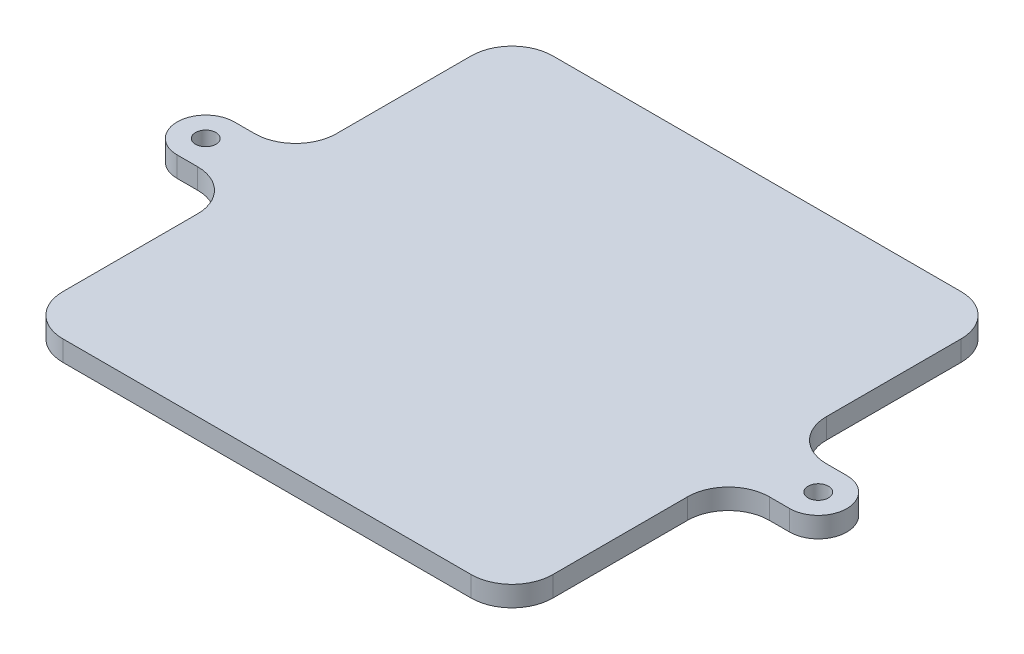
SolidWorks part; units mm, degrees
ref_plane "Front Plane" through (0, 0, 0) normal (0, 0, 1) x (1, 0, 0)
ref_plane "Top Plane" through (0, 0, 0) normal (0, 1, 0) x (1, 0, 0)
ref_plane "Right Plane" through (0, 0, 0) normal (1, 0, 0) x (0, 0, -1)
sketch "Sketch1" plane through (0, 0, 0) normal (0, 1, 0) x (1, 0, 0)
  line L0 (70, -7) -> (75, -7)
  line L1 (-50, -60) -> (50, -60)
  line L2 (-60, -50) -> (-60, -17)
  line L3 (-50, 60) -> (50, 60)
  line L4 (60, -50) -> (60, -17)
  line L7 (70, 7) -> (75, 7)
  line L16 (-60, 17) -> (-60, 50)
  line L17 (-70, 7) -> (-75, 7)
  line L18 (-70, -7) -> (-75, -7)
  line L19 (60, 17) -> (60, 50)
  line L20 (0, 60) -> (0, -60) construction
  line L21 (-75, 0) -> (75, 0) construction
  arc A2 (-75, 7) -> (-75, -7) centre (-75, 0) ccw
  circle A3 centre (-75, 0) radius 2.5
  arc A5 (-60, -17) -> (-70, -7) centre (-70, -17) ccw
  arc A6 (-60, 17) -> (-70, 7) centre (-70, 17) cw
  arc A7 (60, -17) -> (70, -7) centre (70, -17) cw
  arc A8 (75, 7) -> (75, -7) centre (75, 0) cw
  arc A9 (60, 17) -> (70, 7) centre (70, 17) ccw
  circle A10 centre (75, 0) radius 2.5
  arc A11 (-60, 50) -> (-50, 60) centre (-50, 50) cw
  arc A12 (50, 60) -> (60, 50) centre (50, 50) cw
  arc A13 (50, -60) -> (60, -50) centre (50, -50) ccw
  arc A14 (-50, -60) -> (-60, -50) centre (-50, -50) cw
  point P0 (0, 0)
  point P10 (16.1393, -3)
  point P25 (-60, -7)
  point P28 (-60, 7)
  dimension "D2" = 7
  dimension "D3" = 5
  dimension "D4" = 15
  dimension "D5" = 10
  dimension "D6" = 10
extrude "Boss-Extrude2" add sketch "Sketch1" along normal blind 5
